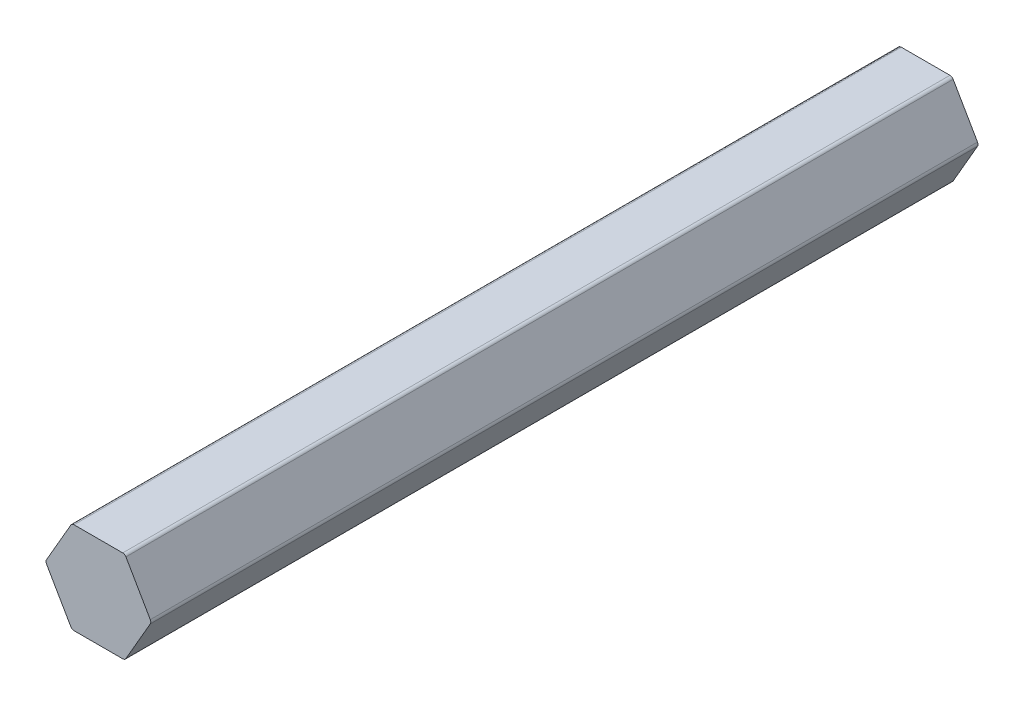
SolidWorks part; units mm, degrees
material "6061 Alloy"
ref_plane "Front Plane" through (0, 0, 0) normal (0, 0, 1) x (1, 0, 0)
ref_plane "Top Plane" through (0, 0, 0) normal (0, 1, 0) x (1, 0, 0)
ref_plane "Right Plane" through (0, 0, 0) normal (1, 0, 0) x (0, 0, -1)
ref_plane "Plane1" through (0, 0, -228.6) normal (0, 0, -1) x (-1, 0, 0)
sketch "Sketch1" plane through (0, 0, -228.6) normal (0, 0, -1) x (-1, 0, 0)
  line L0 (3.8055, -6.0833) -> (7.171, -0.254)
  line L1 (7.171, 0.254) -> (3.8055, 6.0833)
  line L2 (3.3655, 6.3373) -> (-3.3655, 6.3373)
  line L3 (-3.8055, 6.0833) -> (-7.171, 0.254)
  line L4 (-7.171, -0.254) -> (-3.8055, -6.0833)
  line L5 (-3.3655, -6.3373) -> (3.3655, -6.3373)
  arc A0 (3.3655, -6.3373) -> (3.8055, -6.0833) centre (3.3655, -5.8293) ccw
  arc A1 (7.171, -0.254) -> (7.171, 0.254) centre (6.7311, 0) ccw
  arc A2 (3.8055, 6.0833) -> (3.3655, 6.3373) centre (3.3655, 5.8293) ccw
  arc A3 (-3.3655, 6.3373) -> (-3.8055, 6.0833) centre (-3.3655, 5.8293) ccw
  arc A4 (-7.171, 0.254) -> (-7.171, -0.254) centre (-6.7311, 0) ccw
  arc A5 (-3.8055, -6.0833) -> (-3.3655, -6.3373) centre (-3.3655, -5.8293) ccw
extrude "Boss-Extrude1" add sketch "Sketch1" against normal blind 114.3
